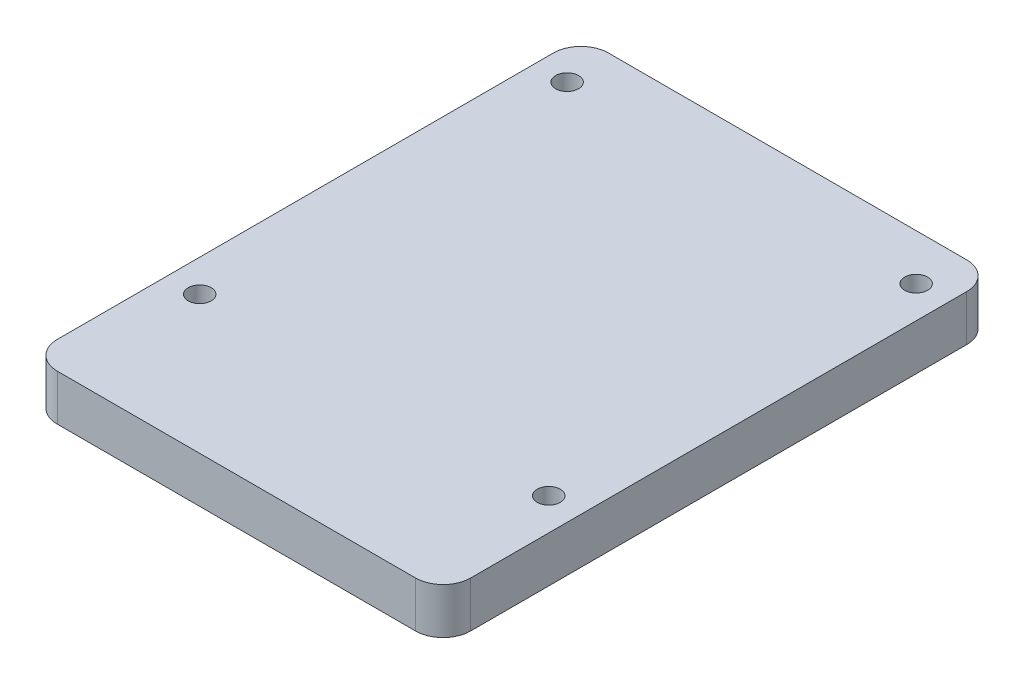
SolidWorks part; units mm, degrees
ref_plane "Front Plane" through (0, 0, 0) normal (0, 0, 1) x (1, 0, 0)
ref_plane "Top Plane" through (0, 0, 0) normal (0, 1, 0) x (1, 0, 0)
ref_plane "Right Plane" through (0, 0, 0) normal (1, 0, 0) x (0, 0, -1)
sketch "Sketch1" plane through (0, 0, 0) normal (0, 1, 0) x (1, 0, 0)
  line L0 (0, 0) -> (0, 5) construction
  line L1 (-22.5, 5) -> (22.5, 5)
  line L2 (-22.5, 5) -> (-22.5, -5) construction
  line L3 (-22.5, -5) -> (22.5, -5) construction
  line L4 (22.5, 5) -> (22.5, -5) construction
  line L5 (-22.5, 5) -> (22.5, -5) construction
  line L6 (-22.5, -5) -> (22.5, 5) construction
  line L7 (0, 0) -> (-22.5, 0) construction
  line L8 (-22.5, 5) -> (-22.5, -55)
  line L9 (-22.5, -25) -> (22.5, -25) construction
  line L10 (-22.5, -25) -> (-22.5, -55) construction
  line L11 (-22.5, -55) -> (22.5, -55) construction
  line L12 (22.5, -25) -> (22.5, -55) construction
  line L13 (-22.5, -25) -> (22.5, -55) construction
  line L14 (-22.5, -55) -> (22.5, -25) construction
  line L15 (-22.5, -55) -> (22.5, -55)
  line L16 (22.5, -55) -> (22.5, 5)
  line L17 (0, -40) -> (-22.5, -40) construction
  circle A0 centre (-19, 0) radius 1.25
  circle A1 centre (19, 0) radius 1.25
  circle A2 centre (-19, -40) radius 1.25
  circle A3 centre (19, -40) radius 1.25
  point P0 (0, 0)
  point P12 (0, -40)
  point P22 (0, 0)
  point P23 (19, -37.8023)
  point P26 (0, 0)
  dimension "D3" = 38
  dimension "D4" = 2.5
  dimension "D1" = 5
  dimension "D2" = 45
  dimension "D5" = 40
  dimension "D6" = 15
extrude "Boss-Extrude1" add sketch "Sketch1" along normal blind 5
fillet "Fillet1" radius 3 4 edges at (-22.5, 2.5, 55) (22.5, 2.5, 55) (22.5, 2.5, -5) (-22.5, 2.5, -5)
